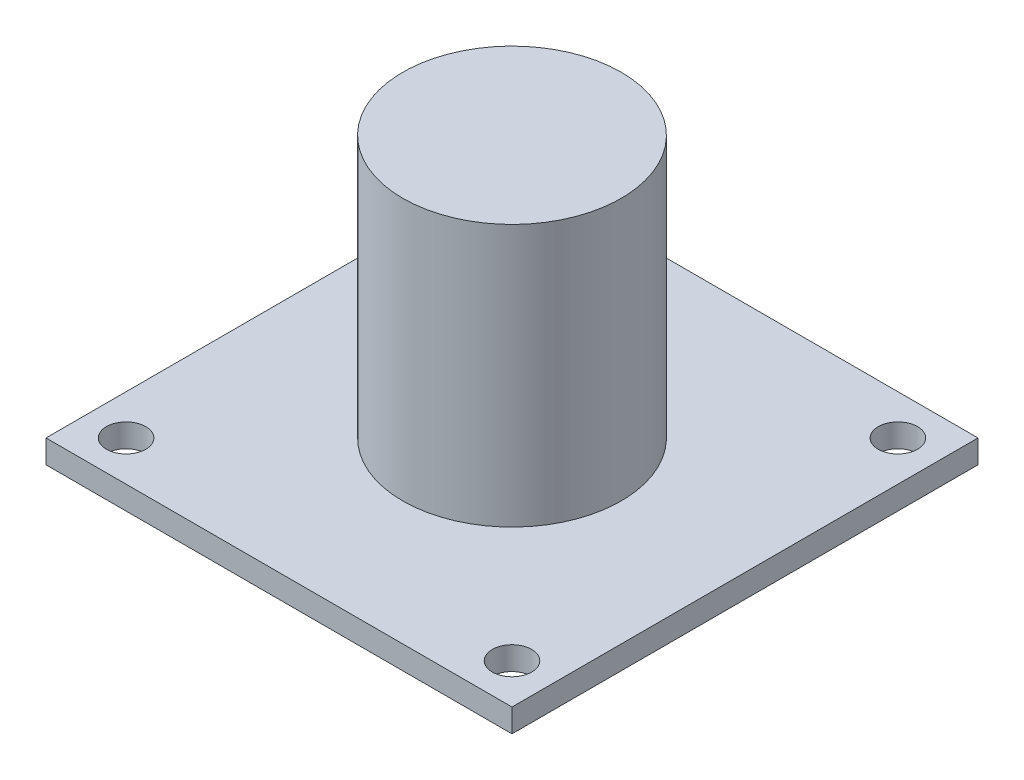
SolidWorks part; units mm, degrees
ref_plane "前视基准面" through (0, 0, 0) normal (0, 0, 1) x (1, 0, 0)
ref_plane "上视基准面" through (0, 0, 0) normal (0, 1, 0) x (1, 0, 0)
ref_plane "右视基准面" through (0, 0, 0) normal (1, 0, 0) x (0, 0, -1)
sketch "草图1" plane through (0, 0, 0) normal (0, 1, 0) x (1, 0, 0)
  line L1 (-16, 16) -> (16, 16)
  line L2 (-16, 16) -> (-16, -16)
  line L3 (-16, -16) -> (16, -16)
  line L4 (16, 16) -> (16, -16)
  line L5 (-16, 16) -> (16, -16) construction
  line L6 (-16, -16) -> (16, 16) construction
  line L7 (-13.25, 13.25) -> (13.25, 13.25) construction
  line L8 (-13.25, 13.25) -> (-13.25, -13.25) construction
  line L9 (-13.25, -13.25) -> (13.25, -13.25) construction
  line L10 (13.25, 13.25) -> (13.25, -13.25) construction
  line L11 (-13.25, 13.25) -> (13.25, -13.25) construction
  line L12 (-13.25, -13.25) -> (13.25, 13.25) construction
  circle A0 centre (-13.25, 13.25) radius 1.35
  circle A1 centre (13.25, 13.25) radius 1.35
  circle A2 centre (-13.25, -13.25) radius 1.35
  circle A3 centre (13.25, -13.25) radius 1.35
  point P0 (0, 0)
  point P6 (0, 0)
  dimension "D5" = 2.7
  dimension "D6" = 2.7
  dimension "D7" = 2.7
  dimension "D8" = 2.7
  dimension "D1" = 32
  dimension "D2" = 32
  dimension "D3" = 26.5
  dimension "D4" = 26.5
extrude "凸台-拉伸1" add sketch "草图1" along normal blind 1.6
ref_plane "基准面1" through (0, 1.6, 0) normal (0, 1, 0) x (1, 0, 0)
sketch "草图2" plane through (0, 1.6, 0) normal (0, 1, 0) x (1, 0, 0)
  circle A0 centre (0, 0) radius 7.5
  dimension "D1" = 15
extrude "凸台-拉伸2" add sketch "草图2" along normal blind 18
ref_plane "基准面2" through (0, 0, 16) normal (0, 0, 1) x (1, 0, 0)
